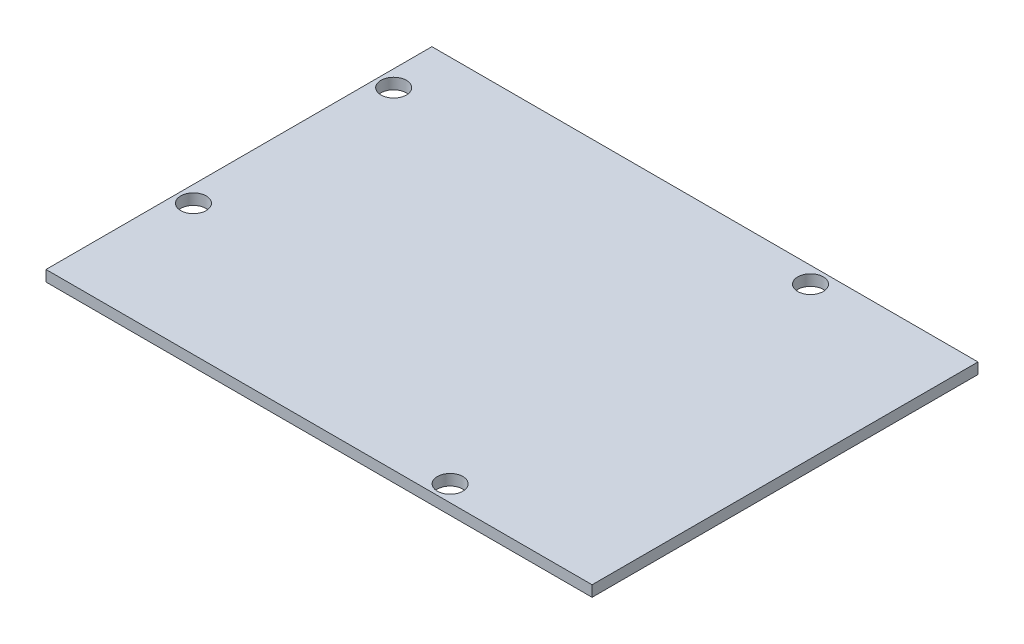
SolidWorks part; units mm, degrees
ref_plane "Front Plane" through (0, 0, 0) normal (0, 0, 1) x (1, 0, 0)
ref_plane "Top Plane" through (0, 0, 0) normal (0, 1, 0) x (1, 0, 0)
ref_plane "Right Plane" through (0, 0, 0) normal (1, 0, 0) x (0, 0, -1)
sketch "Sketch1" plane through (0, 0, 0) normal (0, 1, 0) x (1, 0, 0)
  line L1 (37.5, -26.5) -> (-37.5, -26.5)
  line L2 (37.5, -26.5) -> (37.5, 26.5)
  line L3 (37.5, 26.5) -> (-37.5, 26.5)
  line L4 (-37.5, -26.5) -> (-37.5, 26.5)
  line L5 (37.5, -26.5) -> (-37.5, 26.5) construction
  line L6 (37.5, 26.5) -> (-37.5, -26.5) construction
  circle A0 centre (-35.25, 19) radius 1.75
  circle A1 centre (-35.25, -8.5) radius 1.75
  circle A2 centre (15.75, -24.25) radius 1.75
  circle A3 centre (16.75, 24.25) radius 1.75
  point P0 (0, 0)
  point P16 (6.261, 17.144)
  dimension "D5" = 3.5
  dimension "D6" = 27.5
  dimension "D9" = 52
  dimension "D1" = 75
  dimension "D2" = 53
  dimension "D3" = 7.5
  dimension "D4" = 2.25
  dimension "D7" = 51
  dimension "D8" = 50.75
  dimension "D10" = 2.25
extrude "Boss-Extrude1" add sketch "Sketch1" along normal blind 1.5
